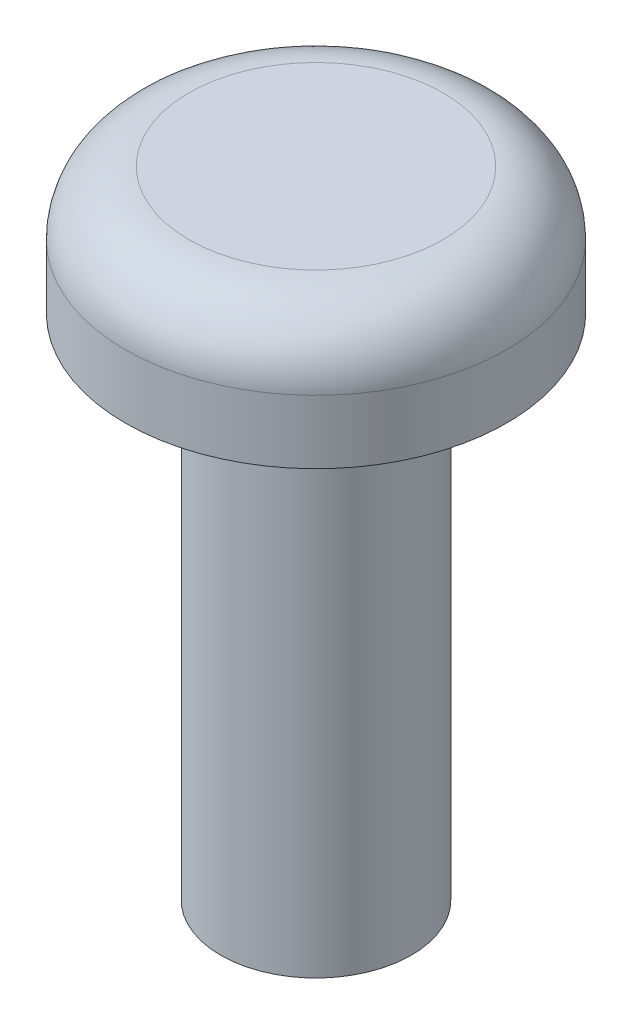
SolidWorks part; units mm, degrees
ref_plane "Front" through (0, 0, 0) normal (0, 0, 1) x (1, 0, 0)
ref_plane "Top" through (0, 0, 0) normal (0, 1, 0) x (1, 0, 0)
ref_plane "Right" through (0, 0, 0) normal (1, 0, 0) x (0, 0, -1)
sketch "Sketch1" plane through (0, 0, 0) normal (0, 1, 0) x (1, 0, 0)
  circle A0 centre (0, 0) radius 1.5
  dimension "D1" = 3
extrude "Boss-Extrude1" add sketch "Sketch1" along normal blind 8
sketch "Sketch2" plane through (0, 8, 0) normal (0, 1, 0) x (1, 0, 0)
  circle A0 centre (0, 0) radius 3
  dimension "D1" = 6
extrude "Boss-Extrude2" add sketch "Sketch2" along normal blind 2
fillet "Fillet1" radius 1 1 edges at (0, 10, 3)
